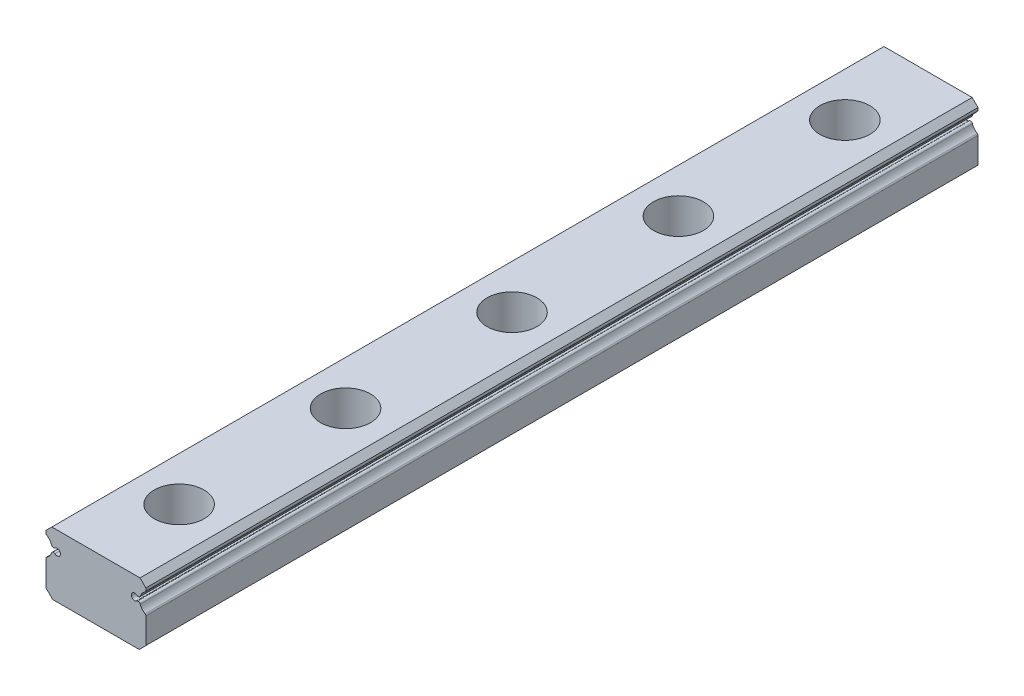
SolidWorks part; units mm, degrees
ref_plane "Front Plane" through (0, 0, 0) normal (0, 0, 1) x (1, 0, 0)
ref_plane "Top Plane" through (0, 0, 0) normal (0, 1, 0) x (1, 0, 0)
ref_plane "Right Plane" through (0, 0, 0) normal (1, 0, 0) x (0, 0, -1)
other "Configuration Table"
sketch "Sketch4" plane through (0, 0, 0) normal (0, 0, 1) x (1, 0, 0)
  line L1 (-6, -7.5) -> (6, -7.5)
  line L2 (-6, -7.5) -> (-6, 0)
  line L3 (-6, 0) -> (6, 0)
  line L4 (6, -7.5) -> (6, 0)
  line L5 (-6, -7.5) -> (6, 0) construction
  line L6 (-6, 0) -> (6, -7.5) construction
  point P0 (0, -3.75)
  dimension "D1" = 12
  dimension "D2" = 7.5
extrude "Boss-Extrude1" add sketch "Sketch4" along normal blind 100
sketch "Sketch5" plane through (0, 0, 0) normal (0, 0, 1) x (1, 0, 0)
  line L0 (-6, -7.5) -> (-6, 0) construction
  line L1 (-6, 0) -> (6, 0) construction
  line L2 (-6, 0) -> (-6, -7.5) construction
  arc A2 (-5.3293, -1.8875) -> (-5.3293, -2.7125) centre (-6.5884, -2.3) ccw
  arc A3 (-4.9276, -1.9982) -> (-4.9276, -2.6018) centre (-4.665, -2.3) cw
  arc A4 (-4.9276, -2.6018) -> (-5.3293, -2.7125) centre (-5.0917, -2.7904) ccw
  arc A5 (-4.9276, -1.9982) -> (-5.3293, -1.8875) centre (-5.0917, -1.8096) cw
  dimension "D2" = 1.325
  dimension "D3" = 0.5884
  dimension "D1" = 0.4
  dimension "D6" = 0.25
  dimension "D4" = 1.335
  dimension "D5" = 2.3
extrude "Cut-Extrude1" cut sketch "Sketch5" along normal through all
mirror "Mirror3" about plane through (0, 0, 0) normal (1, 0, 0) of "Cut-Extrude1"
fillet "Fillet1" radius 0.2 4 edges at (-6, -3.4872, 50) (-6, -1.1128, 50) (6, -1.1128, 50) (6, -3.4872, 50)
chamfer "Chamfer1" distance 0.7 angle 45 2 edges at (-6, 0, 50) (6, 0, 50)
chamfer "Chamfer2" distance 0.8 angle 45 2 edges at (-6, -7.5, 50) (6, -7.5, 50)
sketch "Sketch7" plane through (0, 0, 0) normal (0, 1, 0) x (1, 0, 0)
  point P0 (0, -10)
  dimension "D1" = 10
hole_wizard "CBORE for M3 Hex Socket Head Cap Screw1" positions "Sketch7" profile "Sketch8" counterbore size "M3" standard "DIN" end condition through all
sketch "Sketch8" plane through (0, 0, 10) normal (1, 0, 0) x (0, 0, 1)
  line L0 (0, 0) -> (0, 7.5)
  line L1 (0, 7.5) -> (1.75, 7.5)
  line L3 (1.75, 7.5) -> (1.75, 4.4)
  line L4 (1.75, 4.4) -> (3, 4.4)
  line L5 (3, 4.4) -> (3, 0)
  line L7 (3, 0) -> (0, 0)
  line L11 (0, -6.35) -> (0, 107.95) construction
  dimension "Thru Hole Dia." = 3.5
  dimension "Thru Hole Depth" = 7.5
  dimension "C'Bore Dia." = 6
  dimension "C'Bore Depth" = 4.4
pattern_linear "LPattern1" count 5 spacing 20 along (0, 0, 1) of "CBORE for M3 Hex Socket Head Cap Screw1"
